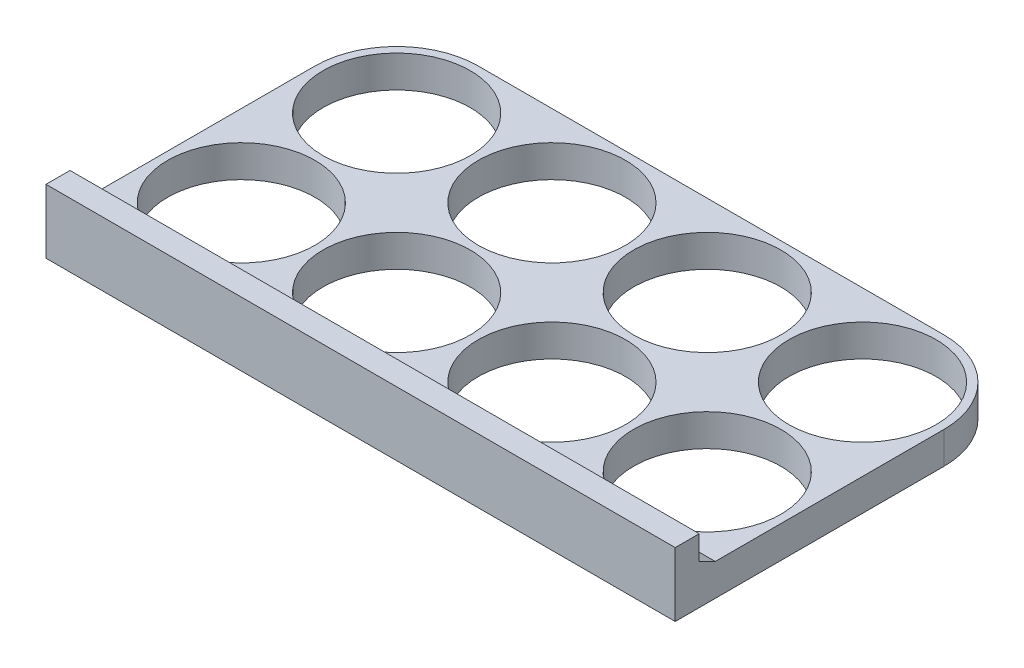
SolidWorks part; units mm, degrees
ref_plane "Front Plane" through (0, 0, 0) normal (0, 0, 1) x (1, 0, 0)
ref_plane "Top Plane" through (0, 0, 0) normal (0, 1, 0) x (1, 0, 0)
ref_plane "Right Plane" through (0, 0, 0) normal (1, 0, 0) x (0, 0, -1)
sketch "Sketch1" plane through (0, 0, 0) normal (0, 1, 0) x (1, 0, 0)
  line L0 (0, 0) -> (58.2, 0) construction
  line L1 (0, 19.4) -> (58.2, 19.4) construction
  line L2 (0, 0) -> (58.2, 19.4) construction
  line L3 (-10.2, 0) -> (-10.2, -14.2)
  line L5 (-10.2, 0) -> (-10.2, 19.4)
  line L6 (0, 29.6) -> (58.2, 29.6)
  line L7 (68.4, 0) -> (68.4, 19.4)
  line L8 (29.1, 29.6) -> (29.1, -9.2) construction
  line L9 (-10.2, 9.7) -> (68.4, 9.7) construction
  line L10 (-10.2, -14.2) -> (68.4, -14.2)
  line L11 (68.4, -14.2) -> (68.4, 0)
  line L12 (0, -9.2) -> (58.2, -9.2) construction
  circle A0 centre (0, 0) radius 9.2
  circle A1 centre (19.4, 0) radius 9.2
  circle A2 centre (38.8, 0) radius 9.2
  circle A3 centre (58.2, 0) radius 9.2
  circle A4 centre (19.4, 19.4) radius 9.2
  circle A5 centre (38.8, 19.4) radius 9.2
  circle A6 centre (58.2, 19.4) radius 9.2
  circle A7 centre (0, 19.4) radius 9.2
  arc A10 (58.2, 29.6) -> (68.4, 19.4) centre (58.2, 19.4) cw
  arc A11 (-10.2, 19.4) -> (0, 29.6) centre (0, 19.4) cw
  point P3 (29.1, 9.7)
  point P4 (29.1, 9.7)
  point P22 (0, 28.6)
  point P23 (0, 0)
  point P25 (68.4, -10.2)
  point P31 (68.4, 29.6)
  point P34 (-10.2, 29.6)
  dimension "D1" = 18.4
  dimension "D2" = 4
  dimension "D4" = 19.4
  dimension "D5" = 19.4
  dimension "D6" = 19.4
  dimension "D8" = 78.6
  dimension "D10" = 5
  dimension "D3" = 2
extrude "Boss-Extrude1" add sketch "Sketch1" along normal blind 4
sketch "Sketch2" plane through (0, 4, 0) normal (0, 1, 0) x (1, 0, 0)
  line L0 (68.4, -14.2) -> (68.4, 19.4) construction
  line L1 (-10.2, -14.2) -> (68.4, -14.2)
  line L2 (-10.2, -14.2) -> (-10.2, -11.2)
  line L3 (-10.2, -11.2) -> (68.4, -11.2)
  line L4 (68.4, -14.2) -> (68.4, -11.2)
  dimension "D1" = 3
extrude "Boss-Extrude2" add sketch "Sketch2" along normal blind 4
ref_plane "Plane1" through (29.1, 0, 0) normal (1, 0, 0) x (0, 0, -1)
sketch "Sketch3" plane through (29.1, 0, 0) normal (1, 0, 0) x (0, 0, -1)
  line L0 (19.4, 4) -> (-11.2, 4) construction
  line L1 (9.2, 4) -> (-9.2, 4) construction
  line L2 (-9.2, 4) -> (-11.2, 5)
  line L3 (-11.2, 8) -> (-11.2, 4) construction
  line L4 (-11.2, 5) -> (-11.2, 4)
  line L5 (-11.2, 4) -> (-9.2, 4)
  point P0 (-9.2, 4)
  point P9 (-11.2, 4)
  point P12 (-11.2, 5)
  dimension "D1" = 1
extrude "Boss-Extrude3" add sketch "Sketch3" along direction (1, 0, 0) on the side of the normal mid plane 78.6
